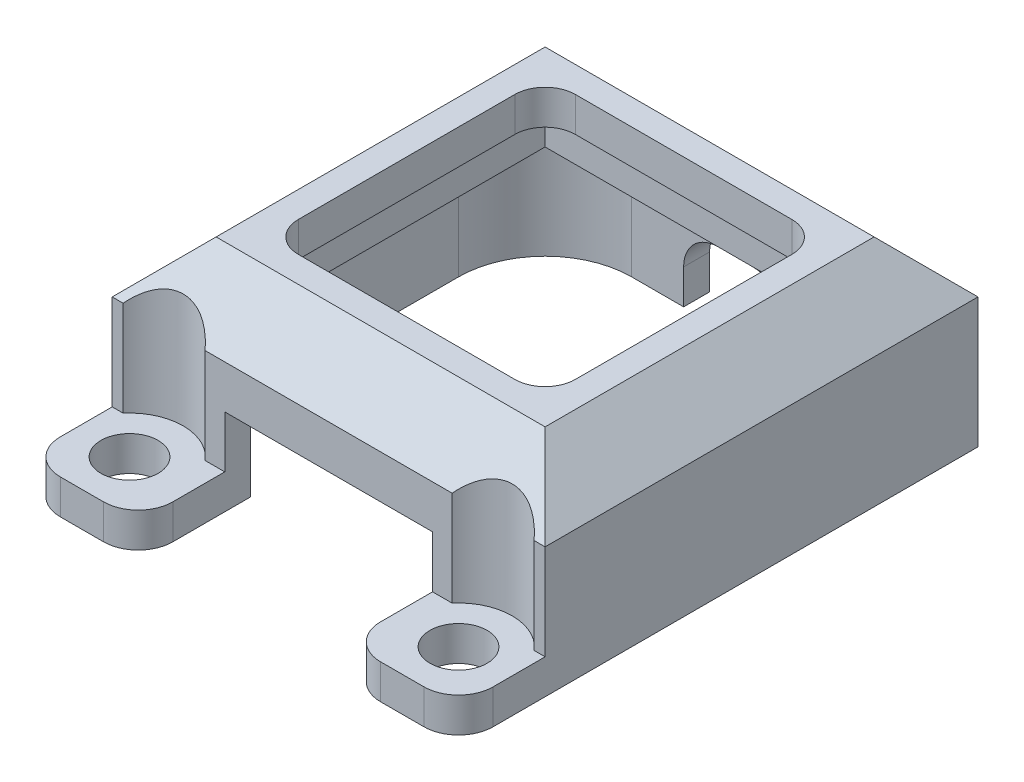
SolidWorks part; units mm, degrees
ref_plane "Płaszczyzna przednia" through (0, 0, 0) normal (0, 0, 1) x (1, 0, 0)
ref_plane "Płaszczyzna górna" through (0, 0, 0) normal (0, 1, 0) x (1, 0, 0)
ref_plane "Płaszczyzna prawa" through (0, 0, 0) normal (1, 0, 0) x (0, 0, -1)
sketch "Szkic1" plane through (0, 0, 0) normal (0, 1, 0) x (1, 0, 0)
  line L0 (-6.25, 8) -> (6.25, 8)
  line L5 (8, 6.25) -> (8, -6.25)
  line L6 (6.25, 8) -> (8, 8) construction
  line L11 (8, 8) -> (8, 6.25) construction
  line L12 (6.25, 8) -> (6.25, 6.25) construction
  line L13 (-6.25, 8) -> (-6.25, 6.25) construction
  line L14 (-8, 6.25) -> (-8, -6.25)
  line L15 (-8, -6.25) -> (-6.25, -6.25) construction
  line L16 (8, -6.25) -> (6.25, -6.25) construction
  line L17 (-6.25, -8) -> (6.25, -8)
  line L18 (0, 8) -> (0, -8) construction
  line L19 (8, 0) -> (-8, 0) construction
  line L21 (-12.5, -12.5) -> (12.5, -12.5)
  line L22 (-12.5, -12.5) -> (-12.5, 12.5)
  line L23 (-12.5, 12.5) -> (12.5, 12.5)
  line L24 (12.5, -12.5) -> (12.5, 12.5)
  line L25 (-12.5, -12.5) -> (12.5, 12.5) construction
  line L26 (-12.5, 12.5) -> (12.5, -12.5) construction
  arc A0 (6.25, 8) -> (8, 6.25) centre (6.25, 6.25) cw
  arc A1 (-6.25, 8) -> (-8, 6.25) centre (-6.25, 6.25) ccw
  arc A2 (8, -6.25) -> (6.25, -8) centre (6.25, -6.25) cw
  arc A3 (-8, -6.25) -> (-6.25, -8) centre (-6.25, -6.25) ccw
  point P5 (0, 0)
  point P18 (0, 0)
  dimension "D7" = 1.75
  dimension "D8" = 1.75
  dimension "D1" = 12.5
  dimension "D2" = 12.5
  dimension "D3" = 1.75
  dimension "D4" = 1.75
  dimension "D5" = 25
  dimension "D6" = 25
extrude "Dodanie-wyciągnięcie1" add sketch "Szkic1" against normal blind 2
sketch "Szkic2" plane through (0, -2, 0) normal (0, -1, 0) x (1, 0, 0)
  line L1 (-8.5, -8.5) -> (8.5, -8.5)
  line L2 (-8.5, -8.5) -> (-8.5, 8.5)
  line L3 (-8.5, 8.5) -> (8.5, 8.5)
  line L4 (8.5, -8.5) -> (8.5, 8.5)
  line L5 (-8.5, -8.5) -> (8.5, 8.5) construction
  line L6 (-8.5, 8.5) -> (8.5, -8.5) construction
  line L7 (-12.5, -12.5) -> (12.5, -12.5)
  line L8 (-12.5, -12.5) -> (-12.5, 12.5)
  line L9 (-12.5, 12.5) -> (12.5, 12.5)
  line L10 (12.5, -12.5) -> (12.5, 12.5)
  line L11 (-12.5, -12.5) -> (12.5, 12.5) construction
  line L12 (-12.5, 12.5) -> (12.5, -12.5) construction
  point P0 (0, 0)
  point P6 (0, 0)
  dimension "D1" = 17
  dimension "D2" = 17
extrude "Dodanie-wyciągnięcie2" add sketch "Szkic2" along normal blind 2
sketch "Szkic3" plane through (0, -4, 0) normal (0, -1, 0) x (1, 0, 0)
  line L1 (-11, -11) -> (11, -11)
  line L2 (-11, -11) -> (-11, 11)
  line L3 (-11, 11) -> (11, 11)
  line L4 (11, -11) -> (11, 11)
  line L5 (-11, -11) -> (11, 11) construction
  line L6 (-11, 11) -> (11, -11) construction
  line L7 (-12.5, -12.5) -> (12.5, -12.5)
  line L8 (-12.5, -12.5) -> (-12.5, 12.5)
  line L9 (-12.5, 12.5) -> (12.5, 12.5)
  line L10 (12.5, -12.5) -> (12.5, 12.5)
  line L11 (-12.5, -12.5) -> (12.5, 12.5) construction
  line L12 (-12.5, 12.5) -> (12.5, -12.5) construction
  point P0 (0, 0)
  point P6 (0, 0)
  dimension "D1" = 22
  dimension "D2" = 22
extrude "Dodanie-wyciągnięcie3" add sketch "Szkic3" along normal blind 6.5
sketch "Szkic4" plane through (0, 0, 12.5) normal (0, 0, 1) x (1, 0, 0)
  line L0 (-6, -5.5) -> (-6, -10.5)
  line L1 (-6, -5.5) -> (6, -5.5)
  line L2 (-6, -10.5) -> (6, -10.5)
  line L3 (6, -5.5) -> (6, -10.5)
  line L4 (-6, -5.5) -> (6, -10.5) construction
  line L5 (-6, -10.5) -> (6, -5.5) construction
  line L6 (12.5, -10.5) -> (-12.5, -10.5) construction
  line L7 (0, -8) -> (0, 0) construction
  point P1 (0, -8)
  dimension "D1" = 5
  dimension "D2" = 12
extrude "Wytnij-wyciągnięcie1" cut sketch "Szkic4" against normal up to surface (1.5 mm away) contours L0 L2 L3 L1 up to face at (0, -7.25, 11)
chamfer "Sfazowanie1" distance 3 angle 45 4 edges at (0, 0, 12.5) (12.5, 0, 0) (0, 0, -12.5) (-12.5, 0, 0)
sketch "Szkic5" plane through (0, -10.5, 0) normal (0, -1, 0) x (1, 0, 0)
  line L0 (-12.5, 12.5) -> (-12.5, 17.5)
  line L1 (-12.5, 17.5) -> (-6, 17.5)
  line L2 (-6, 17.5) -> (-6, 12.5)
  line L3 (-6, 12.5) -> (-12.5, 12.5)
  dimension "D1" = 5
extrude "Dodanie-wyciągnięcie4" add sketch "Szkic5" against normal blind 2
sketch "Szkic8" plane through (0, -10.5, 0) normal (0, -1, 0) x (1, 0, 0)
  line L0 (-12.5, 17.5) -> (-12.5, -12.5) construction
  line L1 (-6, 17.5) -> (-12.5, 17.5) construction
  circle A0 centre (-9.5, 14.5) radius 1.65
  dimension "D2" = 3.3
  dimension "D1" = 3
  dimension "D3" = 3
extrude "Wytnij-wyciągnięcie3" cut sketch "Szkic8" against normal through all
fillet "Zaokrąglenie1" radius 2 2 edges at (-6, -9.5, 17.5) (-12.5, -9.5, 17.5)
sketch "Szkic9" plane through (0, -10.5, 0) normal (0, -1, 0) x (1, 0, 0)
  circle A0 centre (-9.5, 14.5) radius 3.1
  dimension "D1" = 6.2
extrude "Wytnij-wyciągnięcie4" cut sketch "Szkic9" against normal through all from surface at -2 starting at face at (-9.5, -8.5, 16.15)
mirror "Lustro1" about plane through (0, 0, 0) normal (1, 0, 0) of "Wytnij-wyciągnięcie4", "Dodanie-wyciągnięcie4", "Zaokrąglenie1", "Wytnij-wyciągnięcie3"
sketch "Szkic6" plane through (0, 0, -12.5) normal (0, 0, -1) x (-1, 0, 0)
  line L5 (-3, -10.5) -> (3, -10.5)
  line L6 (12.5, -10.5) -> (-12.5, -10.5) construction
  line L7 (3, -10.5) -> (3, -6.5)
  line L8 (3, -6.5) -> (-3, -6.5)
  line L9 (-3, -6.5) -> (-3, -10.5)
  point P5 (0, -10.5)
  dimension "D1" = 4
  dimension "D2" = 6
extrude "Wytnij-wyciągnięcie2" cut sketch "Szkic6" against normal blind 10
fillet "Zaokrąglenie4" radius 2 2 edges at (3, -6.5, -11.75) (-3, -6.5, -11.75)
fillet "Zaokrąglenie5" radius 5 4 edges at (11, -7.25, -11) (-11, -7.25, -11) (-11, -7.25, 11) (11, -7.25, 11)
